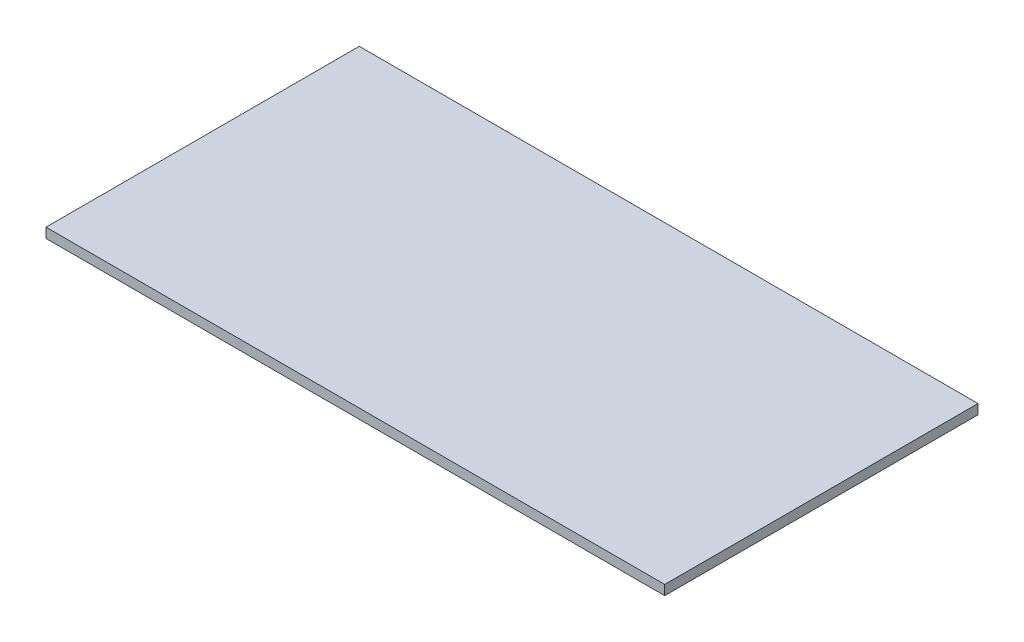
SolidWorks part; units mm, degrees
ref_plane "Front" through (0, 0, 0) normal (0, 0, 1) x (1, 0, 0)
ref_plane "Top" through (0, 0, 0) normal (0, 1, 0) x (1, 0, 0)
ref_plane "Right" through (0, 0, 0) normal (1, 0, 0) x (0, 0, -1)
sketch "Sketch1" plane through (0, 0, 0) normal (0, 1, 0) x (1, 0, 0)
  line L1 (0, 37.8257) -> (200.66, 37.8257)
  line L2 (0, 37.8257) -> (0, 139.4257)
  line L3 (0, 139.4257) -> (200.66, 139.4257)
  line L4 (200.66, 37.8257) -> (200.66, 139.4257)
  dimension "D1" = 200.66
  dimension "D2" = 101.6
extrude "Boss-Extrude1" add sketch "Sketch1" along normal blind 3.175
